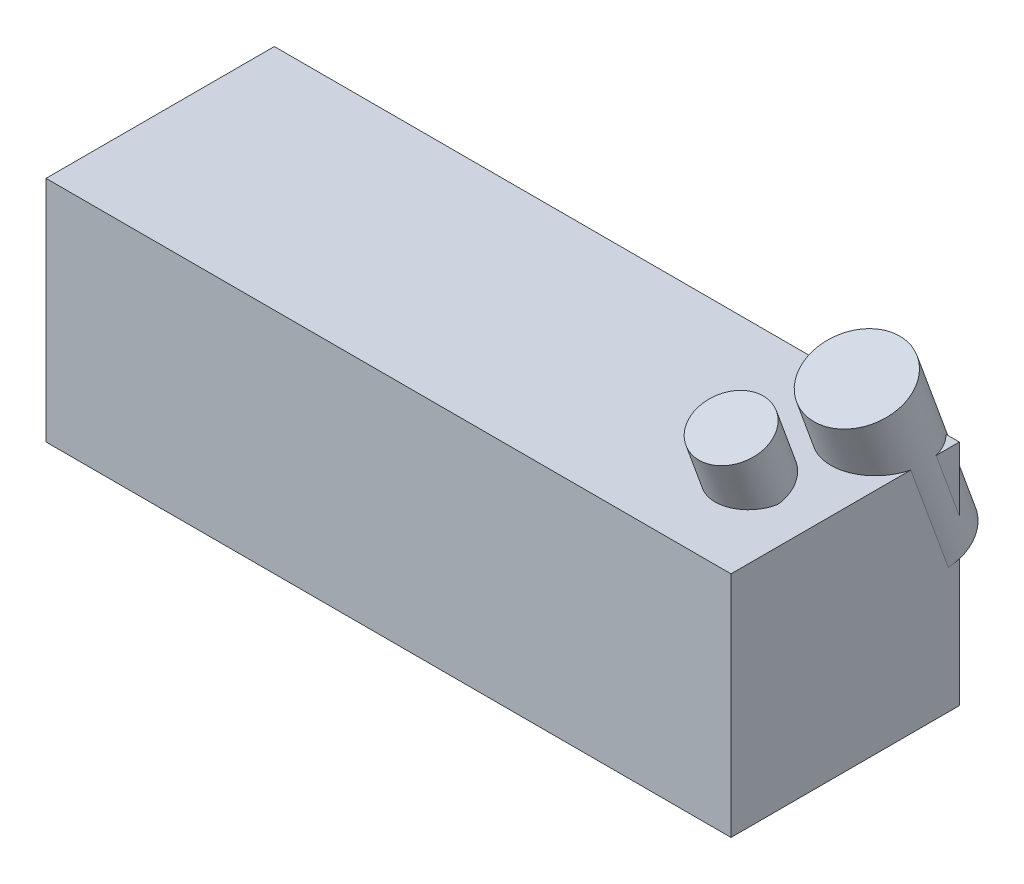
SolidWorks part; units mm, degrees
ref_plane "Front Plane" through (0, 0, 0) normal (0, 0, 1) x (1, 0, 0)
ref_plane "Top Plane" through (0, 0, 0) normal (0, 1, 0) x (1, 0, 0)
ref_plane "Right Plane" through (0, 0, 0) normal (1, 0, 0) x (0, 0, -1)
sketch "Sketch1" plane through (0, 0, 0) normal (0, 0, 1) x (1, 0, 0)
  line L1 (-59.9986, 13.1803) -> (0.0014, 13.1803)
  line L2 (-59.9986, 13.1803) -> (-59.9986, -6.8197)
  line L3 (-59.9986, -6.8197) -> (0.0014, -6.8197)
  line L4 (0.0014, 13.1803) -> (0.0014, -6.8197)
  dimension "D1" = 60
  dimension "D2" = 20
extrude "Boss-Extrude1" add sketch "Sketch1" along normal blind 20
sketch "Sketch2" [suppressed] plane through (0.0788, 0.294, 0) normal (0.2588, 0.9659, 0) x (0.9659, -0.2588, 0)
  circle A0 centre (-5.6677, -20.4027) radius 4
  dimension "D1" = 8
extrude "Boss-Extrude2" [suppressed] add sketch "Sketch2" along normal blind 3
ref_plane "Plane1" through (0, 13.1803, 0) normal (0, 1, 0) x (1, 0, 0)
ref_plane "Plane2" through (0, 18.0664, 6.5756) normal (0, 0.9397, 0.342) x (-1, 0, 0)
sketch "Sketch5" plane through (0, 18.0664, 6.5756) normal (0, 0.9397, 0.342) x (-1, 0, 0)
  circle A0 centre (3.8604, -1.5515) radius 4
extrude "Boss-Extrude5" add sketch "Sketch5" against normal blind 15 contours A0
sketch "Sketch4" plane through (0, 18.0664, 6.5756) normal (0, 0.9397, 0.342) x (-1, 0, 0)
  circle A0 centre (6.1487, 6.8197) radius 3
extrude "Boss-Extrude4" add sketch "Sketch4" along normal mid plane 5 separate body
